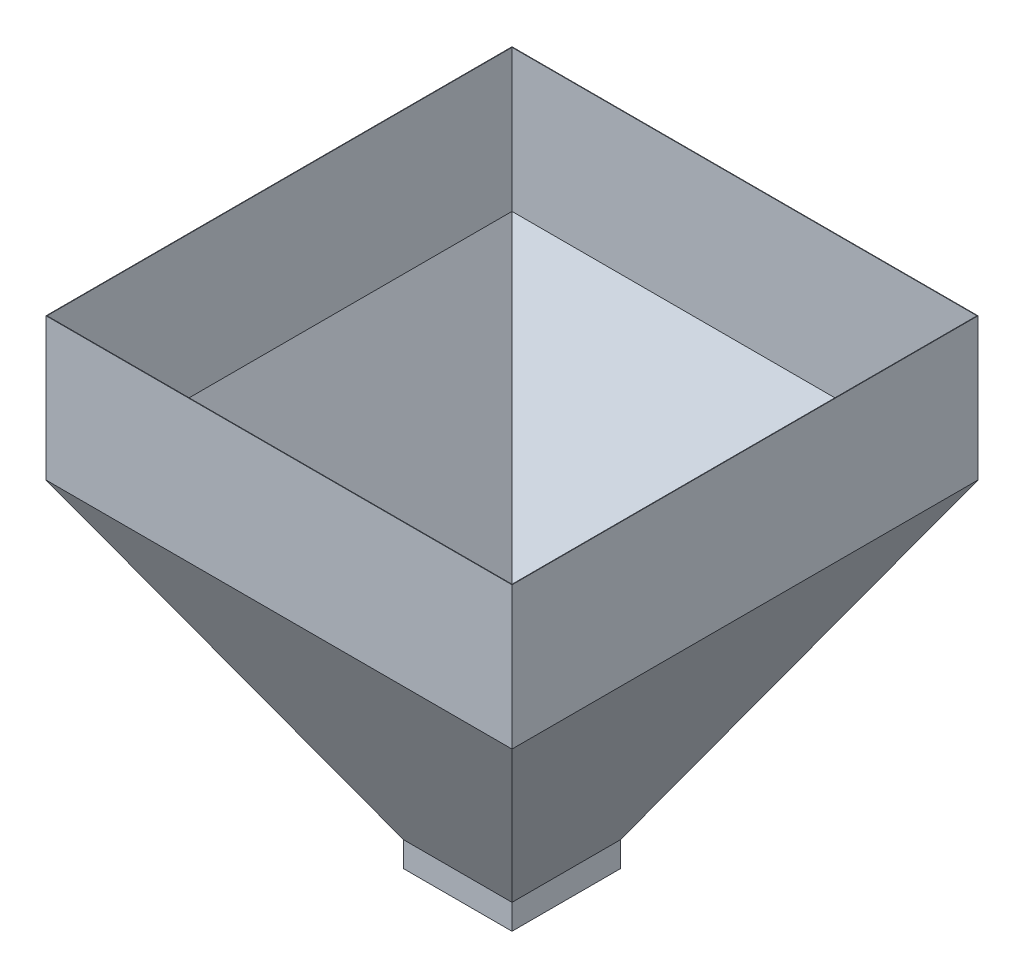
SolidWorks part; units mm, degrees
material "AISI 304"
ref_plane "Alzado" through (0, 0, 0) normal (0, 0, 1) x (1, 0, 0)
ref_plane "Planta" through (0, 0, 0) normal (0, 1, 0) x (1, 0, 0)
ref_plane "Vista lateral" through (0, 0, 0) normal (1, 0, 0) x (0, 0, -1)
sketch "Croquis1" plane through (0, 0, 0) normal (0, 1, 0) x (1, 0, 0)
  line L1 (-344, 344) -> (344, 344)
  line L2 (-344, 344) -> (-344, -344)
  line L3 (-344, -344) -> (344, -344)
  line L4 (344, 344) -> (344, -344)
  line L5 (-344, 344) -> (344, -344) construction
  line L6 (-344, -344) -> (344, 344) construction
  point P0 (0, 0)
  dimension "D1" = 688
ref_plane "Plano1" through (0, -460, 0) normal (0, 1, 0) x (1, 0, 0)
sketch "Croquis2" plane through (0, -460, 0) normal (0, 1, 0) x (1, 0, 0)
  line L0 (-344, 344) -> (344, -344) construction
  line L1 (-80, 80) -> (80, 80)
  line L2 (-80, 80) -> (-80, -80)
  line L3 (-80, -80) -> (80, -80)
  line L4 (80, 80) -> (80, -80)
  line L5 (-80, 80) -> (80, -80) construction
  line L6 (-80, -80) -> (80, 80) construction
  point P0 (0, 0)
  dimension "D1" = 160
loft "Recubrir1" add profiles "Croquis1", "Croquis2"
sketch "Croquis3" plane through (0, 0, 0) normal (0, 1, 0) x (1, 0, 0)
  line L1 (-344, 344) -> (344, 344)
  line L2 (-344, 344) -> (-344, -344)
  line L3 (-344, -344) -> (344, -344)
  line L4 (344, 344) -> (344, -344)
extrude "Saliente-Extruir1" add sketch "Croquis3" along normal blind 210
shell "Vaciado2" thickness 0.76
sketch "Croquis4" plane through (0, -460, 0) normal (0, -1, 0) x (1, 0, 0)
  line L1 (-80, -80) -> (80, -80)
  line L2 (-80, -80) -> (-80, 80)
  line L3 (-80, 80) -> (80, 80)
  line L4 (80, -80) -> (80, 80)
  line L5 (-80, -80) -> (80, 80) construction
  line L6 (-80, 80) -> (80, -80) construction
  line L7 (79.1237, 79.1237) -> (-79.1237, 79.1237)
  line L8 (79.1237, 79.1237) -> (79.1237, -79.1237)
  line L9 (79.1237, -79.1237) -> (-79.1237, -79.1237)
  line L10 (-79.1237, 79.1237) -> (-79.1237, -79.1237)
  line L11 (79.1237, 79.1237) -> (-79.1237, -79.1237) construction
  line L12 (79.1237, -79.1237) -> (-79.1237, 79.1237) construction
  point P4 (0, 0)
  point P11 (0, 0)
extrude "Saliente-Extruir2" add sketch "Croquis4" along normal blind 37
